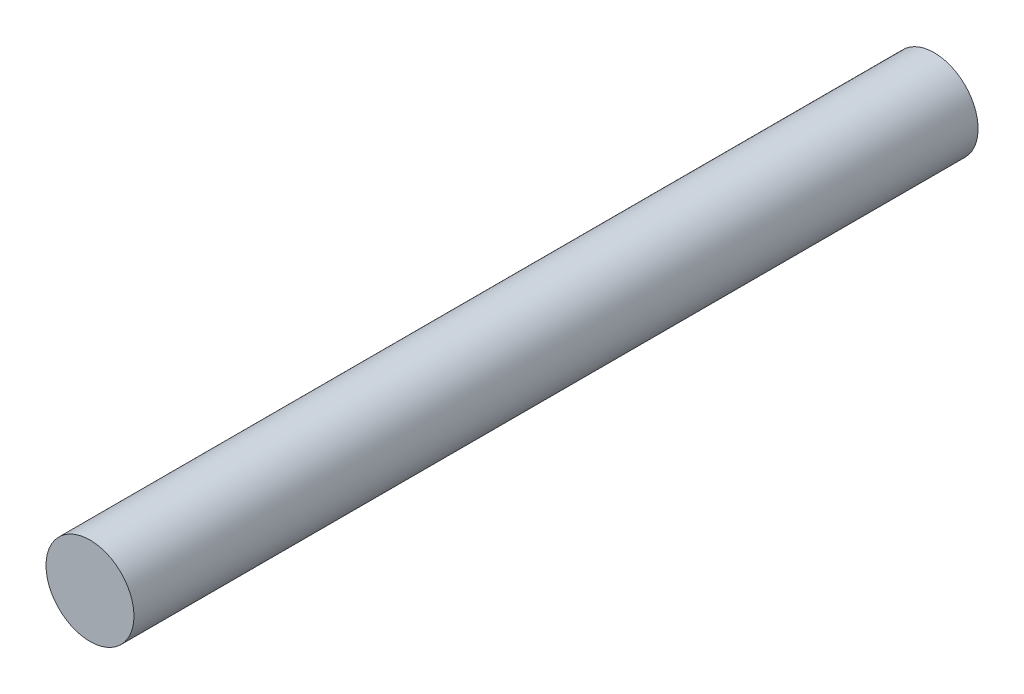
SolidWorks part; units mm, degrees
ref_plane "Front Plane" through (0, 0, 0) normal (0, 0, 1) x (1, 0, 0)
ref_plane "Top Plane" through (0, 0, 0) normal (0, 1, 0) x (1, 0, 0)
ref_plane "Right Plane" through (0, 0, 0) normal (1, 0, 0) x (0, 0, -1)
sketch "Sketch1" plane through (0, 0, 0) normal (0, 0, 1) x (1, 0, 0)
  circle A0 centre (0, 0) radius 3.175
  dimension "D1" = 6.35
extrude "Boss-Extrude1" add sketch "Sketch1" along normal blind 60.96
